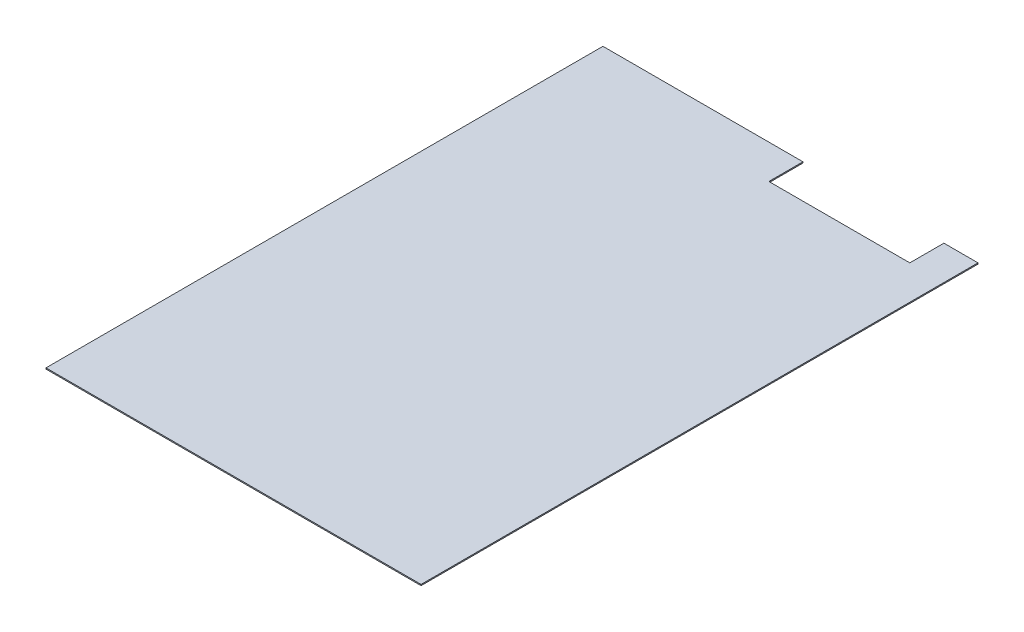
SolidWorks part; units mm, degrees
material "ABS"
ref_plane "Front Plane" through (0, 0, 0) normal (0, 0, 1) x (1, 0, 0)
ref_plane "Top Plane" through (0, 0, 0) normal (0, 1, 0) x (1, 0, 0)
ref_plane "Right Plane" through (0, 0, 0) normal (1, 0, 0) x (0, 0, -1)
sketch "Sketch1" plane through (0, 0, 0) normal (0, 1, 0) x (1, 0, 0)
  line L1 (-82.5, 122.5) -> (82.5, 122.5)
  line L2 (-82.5, 122.5) -> (-82.5, -122.5)
  line L3 (-82.5, -122.5) -> (82.5, -122.5)
  line L4 (82.5, 122.5) -> (82.5, -122.5)
  line L5 (-82.5, 122.5) -> (82.5, -122.5) construction
  line L6 (-82.5, -122.5) -> (82.5, 122.5) construction
  point P0 (0, 0)
  dimension "D1" = 245
  dimension "D2" = 165
extrude "Boss-Extrude1" add sketch "Sketch1" along normal blind 0.5
sketch "Sketch2" plane through (0, 0, 0) normal (0, -1, 0) x (1, 0, 0)
  line L0 (67.5, -122.5) -> (67.5, -107.5)
  line L1 (82.5, -122.5) -> (-82.5, -122.5) construction
  line L2 (67.5, -107.5) -> (5.5, -107.5)
  line L3 (5.5, -107.5) -> (5.5, -122.5)
  line L4 (5.5, -122.5) -> (67.5, -122.5)
  line L5 (82.5, 122.5) -> (82.5, -122.5) construction
  dimension "D1" = 15
  dimension "D2" = 62
  dimension "D3" = 15
extrude "Cut-Extrude1" cut sketch "Sketch2" against normal blind 10 contours L0 L2 L3 L4
